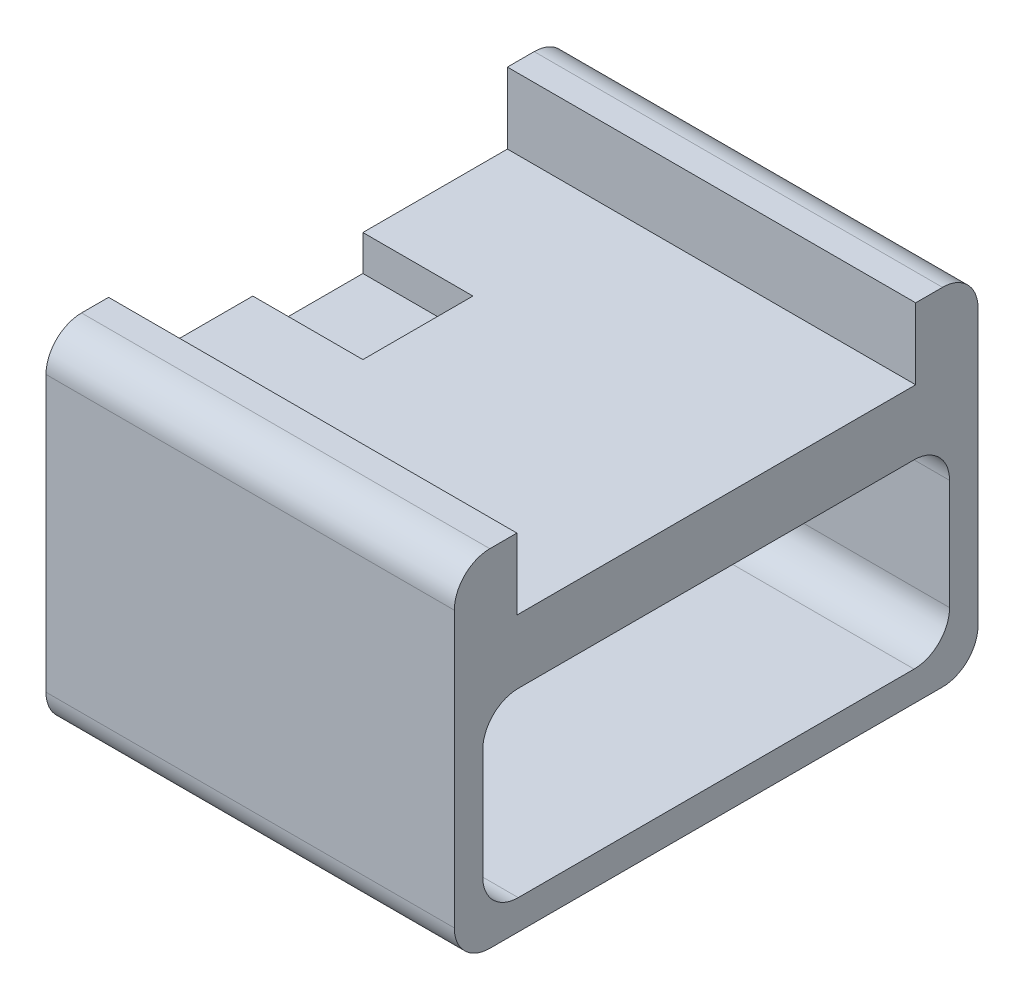
SolidWorks part; units mm, degrees
ref_plane "Front Plane" through (0, 0, 0) normal (0, 0, 1) x (1, 0, 0)
ref_plane "Top Plane" through (0, 0, 0) normal (0, 1, 0) x (1, 0, 0)
ref_plane "Right Plane" through (0, 0, 0) normal (1, 0, 0) x (0, 0, -1)
sketch "Sketch3" plane through (0, 0, 0) normal (1, 0, 0) x (0, 0, -1)
  line L0 (-12.75, -9.75) -> (12.75, -9.75)
  line L1 (-14.75, -7.75) -> (-14.75, 7.75)
  line L2 (-12.75, 9.75) -> (12.75, 9.75)
  line L3 (14.75, -7.75) -> (14.75, 7.75)
  line L4 (0, 9.75) -> (0, -9.75) construction
  line L5 (14.75, 0) -> (-14.75, 0) construction
  arc A0 (14.75, -7.75) -> (12.75, -9.75) centre (12.75, -7.75) cw
  arc A1 (-14.75, -7.75) -> (-12.75, -9.75) centre (-12.75, -7.75) ccw
  arc A2 (-12.75, 9.75) -> (-14.75, 7.75) centre (-12.75, 7.75) ccw
  arc A3 (12.75, 9.75) -> (14.75, 7.75) centre (12.75, 7.75) cw
  point P16 (0, 0)
  dimension "D3" = 2
  dimension "D1" = 19.5
  dimension "D2" = 25.5
extrude "Boss-Extrude1" add sketch "Sketch3" along normal blind 23
sketch "Sketch5" plane through (0, 9.75, 0) normal (0, 1, 0) x (1, 0, 0)
  line L0 (0, 12.75) -> (0, -12.75) construction
  line L1 (6.2, 3.1) -> (0, 3.1)
  line L2 (6.2, 3.1) -> (6.2, -3.1)
  line L3 (6.2, -3.1) -> (0, -3.1)
  line L4 (0, 3.1) -> (0, -3.1)
  line L5 (6.2, 0) -> (0, 0) construction
  dimension "D1" = 6.2
  dimension "D2" = 6.2
extrude "Cut-Extrude1" cut sketch "Sketch5" against normal blind 6
sketch "Sketch7" plane through (0, 0, 0) normal (-1, 0, 0) x (0, 0, 1)
  line L0 (0, 2.1353) -> (0, -8.0729) construction
  line L1 (-11.1476, -8.0729) -> (11.1476, -8.0729)
  line L2 (-13.1476, -6.0729) -> (-13.1476, 0.1353)
  line L3 (-11.1476, 2.1353) -> (11.1476, 2.1353)
  line L4 (13.1476, -6.0729) -> (13.1476, 0.1353)
  line L5 (12.75, -9.75) -> (-12.75, -9.75) construction
  arc A0 (11.1476, -8.0729) -> (13.1476, -6.0729) centre (11.1476, -6.0729) ccw
  arc A1 (11.1476, 2.1353) -> (13.1476, 0.1353) centre (11.1476, 0.1353) cw
  arc A2 (-13.1476, 0.1353) -> (-11.1476, 2.1353) centre (-11.1476, 0.1353) cw
  arc A3 (-13.1476, -6.0729) -> (-11.1476, -8.0729) centre (-11.1476, -6.0729) ccw
  point P6 (0, -2.9688)
  point P7 (0, -9.75)
  dimension "D1" = 2
extrude "Cut-Extrude2" cut sketch "Sketch7" against normal through all both and the other way through all
sketch "Sketch9" plane through (0, 9.75, 0) normal (0, 1, 0) x (1, 0, 0)
  line L0 (0, 12.75) -> (0, 3.1) construction
  line L1 (0, 11.24) -> (24.2849, 11.24)
  line L2 (0, 11.24) -> (0, -11.2248)
  line L3 (0, -11.2248) -> (24.2849, -11.2248)
  line L4 (24.2849, 11.24) -> (24.2849, -11.2248)
  line L5 (24.2849, 0.0076) -> (0, 0.0076) construction
  line L6 (6.2, -3.1) -> (6.2, 3.1) construction
  point P8 (6.2, 0)
  point P12 (6.2, -0.2283)
extrude "Cut-Extrude3" cut sketch "Sketch9" against normal blind 4
